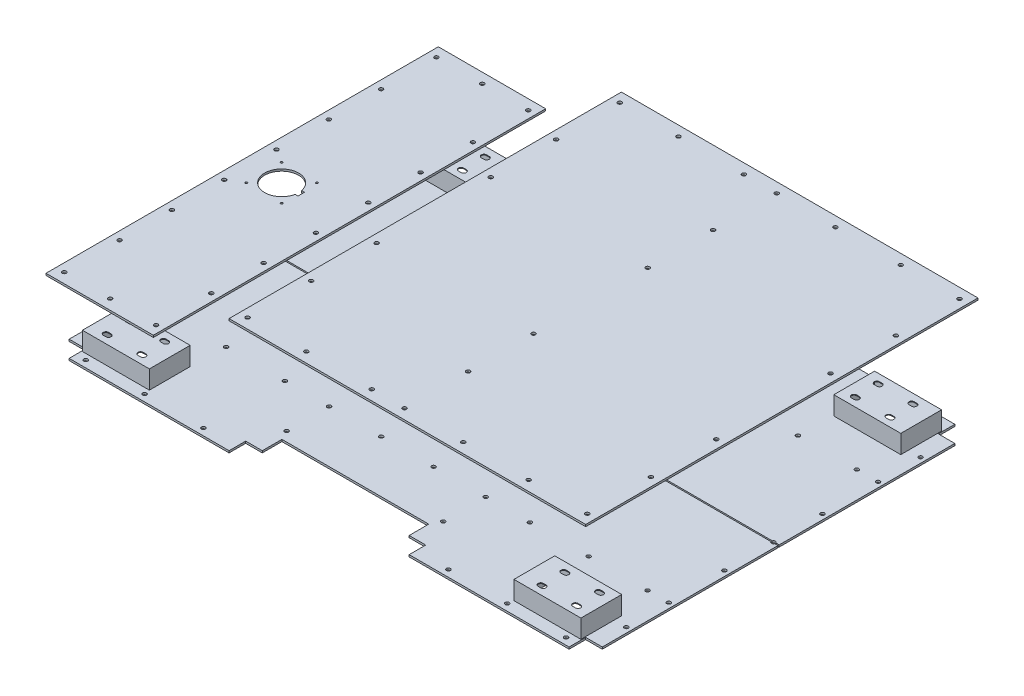
SolidWorks part; units mm, degrees
ref_plane "Front Plane" through (0, 0, 0) normal (0, 0, 1) x (1, 0, 0)
ref_plane "Top Plane" through (0, 0, 0) normal (0, 1, 0) x (1, 0, 0)
ref_plane "Right Plane" through (0, 0, 0) normal (1, 0, 0) x (0, 0, -1)
sketch "Sketch2" plane through (0, 422.0595, 0) normal (0, 1, 0) x (1, 0, 0)
  line L0 (436.2951, -933.6952) -> (410.8951, -933.6952) construction
  line L9 (436.2951, -933.6952) -> (410.8951, -933.6952) construction
  line L11 (196.2951, -933.6952) -> (196.2951, -903.6952) construction
  line L19 (196.2951, -834.4952) -> (196.2951, -933.6952) construction
  line L21 (196.2951, -903.6952) -> (410.8951, -903.6952) construction
  line L22 (410.8951, -933.6952) -> (410.8951, -834.4952) construction
  line L72 (410.8951, -903.6952) -> (410.8951, -933.6952) construction
  line L73 (436.2951, -959.0952) -> (436.2951, -933.6952) construction
  line L76 (690.8951, -959.0952) -> (436.2951, -959.0952) construction
  line L78 (690.8951, -933.6952) -> (690.8951, -959.0952) construction
  line L79 (410.8951, -384.4952) -> (436.2951, -384.4952) construction
  line L80 (436.2951, -384.4952) -> (436.2951, -359.0952) construction
  line L81 (436.2951, -359.0952) -> (690.8951, -359.0952) construction
  line L82 (436.2951, -959.0952) -> (436.2951, -933.6952) construction
  line L83 (690.8951, -959.0952) -> (436.2951, -959.0952) construction
  line L84 (690.8951, -933.6952) -> (690.8951, -959.0952) construction
  line L85 (690.8951, -359.0952) -> (690.8951, -384.4952) construction
  line L86 (690.8951, -384.4952) -> (716.2951, -384.4952) construction
  line L87 (716.2951, -384.4952) -> (716.2951, -933.6952) construction
  line L88 (716.2951, -933.6952) -> (690.8951, -933.6952) construction
  line L89 (410.8951, -384.4952) -> (436.2951, -384.4952) construction
  line L90 (436.2951, -384.4952) -> (436.2951, -359.0952) construction
  line L91 (436.2951, -359.0952) -> (690.8951, -359.0952) construction
  line L92 (690.8951, -359.0952) -> (690.8951, -384.4952) construction
  line L93 (690.8951, -384.4952) -> (716.2951, -384.4952) construction
  line L94 (716.2951, -384.4952) -> (716.2951, -658.0952) construction
  line L95 (716.2951, -933.6952) -> (690.8951, -933.6952) construction
  line L96 (196.2951, -933.6952) -> (170.8951, -933.6952) construction
  line L97 (170.8951, -933.6952) -> (170.8951, -959.0952) construction
  line L98 (170.8951, -959.0952) -> (-83.7049, -959.0952) construction
  line L99 (-83.7049, -959.0952) -> (-83.7049, -933.6952) construction
  line L100 (-83.7049, -933.6952) -> (-109.1049, -933.6952) construction
  line L101 (-109.1049, -933.6952) -> (-109.1049, -384.4952) construction
  line L102 (-109.1049, -384.4952) -> (-83.7049, -384.4952) construction
  line L103 (-83.7049, -384.4952) -> (-83.7049, -359.0952) construction
  line L104 (-83.7049, -359.0952) -> (170.8951, -359.0952) construction
  line L105 (170.8951, -359.0952) -> (170.8951, -384.4952) construction
  line L106 (170.8951, -384.4952) -> (196.2951, -384.4952) construction
  line L107 (196.2951, -933.6952) -> (170.8951, -933.6952) construction
  line L108 (170.8951, -933.6952) -> (170.8951, -959.0952) construction
  line L109 (170.8951, -959.0952) -> (-83.7049, -959.0952) construction
  line L110 (-83.7049, -959.0952) -> (-83.7049, -933.6952) construction
  line L111 (-83.7049, -933.6952) -> (-109.1049, -933.6952) construction
  line L112 (-109.1049, -933.6952) -> (-109.1049, -660.0952) construction
  line L113 (-109.1049, -384.4952) -> (-83.7049, -384.4952) construction
  line L114 (-83.7049, -384.4952) -> (-83.7049, -359.0952) construction
  line L115 (-83.7049, -359.0952) -> (170.8951, -359.0952) construction
  line L116 (170.8951, -359.0952) -> (170.8951, -384.4952) construction
  line L117 (170.8951, -384.4952) -> (196.2951, -384.4952) construction
  line L118 (716.2951, -659.0952) -> (-109.1049, -659.0952) construction
  line L119 (196.2951, -384.4952) -> (196.2951, -414.4952) construction
  line L120 (196.2951, -384.4952) -> (196.2951, -483.6952) construction
  line L121 (196.2951, -414.4952) -> (410.8951, -414.4952) construction
  line L122 (410.8951, -483.6952) -> (410.8951, -384.4952) construction
  line L123 (410.8951, -414.4952) -> (410.8951, -384.4952) construction
  line L124 (716.2951, -658.0952) -> (-109.1049, -658.0952) construction
  line L125 (716.2951, -660.0952) -> (-109.1049, -660.0952) construction
  line L126 (716.2951, -660.0952) -> (716.2951, -933.6952) construction
  line L127 (-109.1049, -658.0952) -> (-109.1049, -384.4952) construction
  line L128 (711.2951, -660.0952) -> (711.2951, -928.6952)
  line L129 (711.2951, -928.6952) -> (685.8951, -928.6952)
  line L130 (685.8951, -928.6952) -> (685.8951, -954.0952)
  line L131 (685.8951, -954.0952) -> (441.2951, -954.0952)
  line L132 (441.2951, -954.0952) -> (441.2951, -928.6952)
  line L133 (441.2951, -928.6952) -> (415.8951, -928.6952)
  line L134 (415.8951, -898.6952) -> (415.8951, -928.6952)
  line L135 (191.2951, -898.6952) -> (415.8951, -898.6952)
  line L136 (191.2951, -928.6952) -> (191.2951, -898.6952)
  line L137 (191.2951, -928.6952) -> (165.8951, -928.6952)
  line L138 (165.8951, -928.6952) -> (165.8951, -954.0952)
  line L139 (165.8951, -954.0952) -> (-78.7049, -954.0952)
  line L140 (-78.7049, -954.0952) -> (-78.7049, -928.6952)
  line L141 (-78.7049, -928.6952) -> (-104.1049, -928.6952)
  line L142 (-104.1049, -928.6952) -> (-104.1049, -660.0952)
  line L143 (-104.1049, -658.0952) -> (-104.1049, -389.4952)
  line L144 (-104.1049, -389.4952) -> (-78.7049, -389.4952)
  line L145 (-78.7049, -389.4952) -> (-78.7049, -364.0952)
  line L146 (-78.7049, -364.0952) -> (165.8951, -364.0952)
  line L147 (165.8951, -364.0952) -> (165.8951, -389.4952)
  line L148 (165.8951, -389.4952) -> (191.2951, -389.4952)
  line L149 (191.2951, -389.4952) -> (191.2951, -419.4952)
  line L150 (191.2951, -419.4952) -> (415.8951, -419.4952)
  line L151 (415.8951, -419.4952) -> (415.8951, -389.4952)
  line L152 (415.8951, -389.4952) -> (441.2951, -389.4952)
  line L153 (441.2951, -389.4952) -> (441.2951, -364.0952)
  line L154 (441.2951, -364.0952) -> (685.8951, -364.0952)
  line L155 (685.8951, -364.0952) -> (685.8951, -389.4952)
  line L156 (685.8951, -389.4952) -> (711.2951, -389.4952)
  line L157 (711.2951, -389.4952) -> (711.2951, -658.0952)
  line L158 (-104.1049, -660.0952) -> (711.2951, -660.0952)
  line L159 (711.2951, -658.0952) -> (-104.1049, -658.0952)
  circle A0 centre (703.3951, -434.0952) radius 3 construction
  circle A1 centre (703.3951, -499.0952) radius 3 construction
  circle A2 centre (183.7951, -884.0952) radius 3 construction
  circle A3 centre (183.7951, -819.0952) radius 3 construction
  circle A5 centre (703.3951, -499.0952) radius 3
  circle A6 centre (703.3951, -434.0952) radius 3
  circle A7 centre (703.3951, -819.0952) radius 3 construction
  circle A8 centre (703.3951, -734.0952) radius 3 construction
  circle A9 centre (703.3951, -659.0952) radius 3 construction
  circle A10 centre (703.3951, -584.0952) radius 3 construction
  circle A11 centre (703.3951, -819.0952) radius 3
  circle A12 centre (703.3951, -734.0952) radius 3
  circle A13 centre (703.3951, -659.0952) radius 3
  circle A14 centre (703.3951, -584.0952) radius 3
  circle A15 centre (703.3951, -884.0952) radius 3 construction
  circle A16 centre (703.3951, -884.0952) radius 3
  circle A17 centre (116.2951, -943.6952) radius 3 construction
  circle A18 centre (490.8951, -943.6952) radius 3 construction
  circle A19 centre (580.8951, -943.6952) radius 3 construction
  circle A20 centre (670.8951, -943.6952) radius 3 construction
  circle A21 centre (116.2951, -943.6952) radius 3
  circle A22 centre (490.8951, -943.6952) radius 3
  circle A23 centre (580.8951, -943.6952) radius 3
  circle A24 centre (670.8951, -943.6952) radius 3
  circle A25 centre (26.2951, -943.6952) radius 3 construction
  circle A26 centre (26.2951, -943.6952) radius 3
  circle A27 centre (-63.7049, -943.6952) radius 3 construction
  circle A28 centre (-63.7049, -943.6952) radius 3
  circle A29 centre (-63.7049, -819.0952) radius 3 construction
  circle A30 centre (-96.2049, -884.0952) radius 3 construction
  circle A31 centre (-63.7049, -819.0952) radius 3
  circle A32 centre (-96.2049, -884.0952) radius 3
  circle A33 centre (-96.2049, -434.0952) radius 3 construction
  circle A34 centre (-96.2049, -584.0952) radius 3 construction
  circle A35 centre (-96.2049, -659.0952) radius 3 construction
  circle A36 centre (-96.2049, -734.0952) radius 3 construction
  circle A37 centre (-96.2049, -819.0952) radius 3 construction
  circle A38 centre (-96.2049, -434.0952) radius 3
  circle A39 centre (-96.2049, -584.0952) radius 3
  circle A40 centre (-96.2049, -659.0952) radius 3
  circle A41 centre (-96.2049, -734.0952) radius 3
  circle A42 centre (-96.2049, -819.0952) radius 3
  circle A43 centre (-96.2049, -499.0952) radius 3 construction
  circle A44 centre (26.2951, -499.0952) radius 3 construction
  circle A45 centre (-63.7049, -499.0952) radius 3 construction
  circle A46 centre (26.2951, -499.0952) radius 3
  circle A47 centre (-63.7049, -499.0952) radius 3
  circle A48 centre (-96.2049, -499.0952) radius 3
  circle A49 centre (116.2951, -499.0952) radius 3 construction
  circle A50 centre (116.2951, -499.0952) radius 3
  circle A51 centre (-63.7049, -374.4952) radius 3 construction
  circle A52 centre (26.2951, -374.4952) radius 3 construction
  circle A53 centre (116.2951, -374.4952) radius 3 construction
  circle A54 centre (-63.7049, -374.4952) radius 3
  circle A55 centre (26.2951, -374.4952) radius 3
  circle A56 centre (116.2951, -374.4952) radius 3
  circle A57 centre (183.7951, -584.0952) radius 3 construction
  circle A58 centre (183.7951, -499.0952) radius 3 construction
  circle A59 centre (183.7951, -434.0952) radius 3 construction
  circle A60 centre (183.7951, -584.0952) radius 3
  circle A61 centre (183.7951, -499.0952) radius 3
  circle A62 centre (183.7951, -434.0952) radius 3
  circle A63 centre (183.7951, -659.0952) radius 3 construction
  circle A64 centre (183.7951, -659.0952) radius 3
  circle A65 centre (183.7951, -734.0952) radius 3 construction
  circle A66 centre (183.7951, -734.0952) radius 3
  circle A67 centre (263.5951, -819.0952) radius 3 construction
  circle A68 centre (183.7951, -884.0952) radius 3
  circle A69 centre (183.7951, -819.0952) radius 3
  circle A70 centre (263.5951, -819.0952) radius 3
  circle A71 centre (343.5951, -819.0952) radius 3 construction
  circle A72 centre (343.5951, -819.0952) radius 3
  circle A73 centre (423.3951, -884.0952) radius 3 construction
  circle A74 centre (423.3951, -819.0952) radius 3 construction
  circle A75 centre (490.8951, -819.0952) radius 3 construction
  circle A76 centre (423.3951, -734.0952) radius 3 construction
  circle A77 centre (423.3951, -884.0952) radius 3
  circle A78 centre (423.3951, -819.0952) radius 3
  circle A79 centre (490.8951, -819.0952) radius 3
  circle A80 centre (423.3951, -734.0952) radius 3
  circle A81 centre (423.3951, -659.0952) radius 3 construction
  circle A82 centre (423.3951, -659.0952) radius 3
  circle A83 centre (670.8951, -819.0952) radius 3 construction
  circle A84 centre (580.8951, -819.0952) radius 3 construction
  circle A85 centre (670.8951, -819.0952) radius 3
  circle A86 centre (580.8951, -819.0952) radius 3
  circle A87 centre (490.8951, -374.4952) radius 3 construction
  circle A88 centre (580.8951, -374.4952) radius 3 construction
  circle A89 centre (670.8951, -374.4952) radius 3 construction
  circle A90 centre (490.8951, -374.4952) radius 3
  circle A91 centre (580.8951, -374.4952) radius 3
  circle A92 centre (670.8951, -374.4952) radius 3
  circle A93 centre (423.3951, -584.0952) radius 3 construction
  circle A94 centre (423.3951, -584.0952) radius 3
  circle A95 centre (423.3951, -434.0952) radius 3 construction
  circle A96 centre (423.3951, -434.0952) radius 3
  circle A97 centre (423.3951, -499.0952) radius 3 construction
  circle A98 centre (423.3951, -499.0952) radius 3
  circle A99 centre (343.5951, -499.0952) radius 3 construction
  circle A100 centre (343.5951, -499.0952) radius 3
  circle A101 centre (263.5951, -499.0952) radius 3 construction
  circle A102 centre (263.5951, -499.0952) radius 3
  circle A103 centre (670.8951, -499.0952) radius 3 construction
  circle A104 centre (580.8951, -499.0952) radius 3 construction
  circle A105 centre (490.8951, -499.0952) radius 3 construction
  circle A106 centre (670.8951, -499.0952) radius 3
  circle A107 centre (580.8951, -499.0952) radius 3
  circle A108 centre (490.8951, -499.0952) radius 3
  circle A109 centre (116.2951, -819.0952) radius 3 construction
  circle A110 centre (26.2951, -819.0952) radius 3 construction
  circle A111 centre (116.2951, -819.0952) radius 3
  circle A112 centre (26.2951, -819.0952) radius 3
  point P56 (712.1088, -386.4469)
  point P57 (713.2951, -659.0952)
  point P72 (-106.1049, -387.4952)
  point P73 (-106.1049, -930.6952)
  point P88 (0, 0)
  point P90 (-109.1049, -658.0952)
  point P92 (-109.1049, -660.0952)
  dimension "D1" = 30
  dimension "D2" = 30
  dimension "D5" = 300
  dimension "D6" = 5
  dimension "D3" = 1
  dimension "D4" = 1
extrude "Boss-Extrude1" add sketch "Sketch2" along normal blind 3
sketch "Sketch4" plane through (0, 602.0595, 0) normal (0, 1, 0) x (1, 0, 0)
  line L0 (716.2951, -359.0952) -> (170.8951, -359.0952) construction
  line L1 (170.8951, -359.0952) -> (170.8951, -959.0952) construction
  line L2 (170.8951, -933.6952) -> (170.8951, -384.4952) construction
  line L3 (716.2951, -959.0952) -> (716.2951, -359.0952) construction
  line L4 (170.8951, -959.0952) -> (716.2951, -959.0952) construction
  line L5 (716.2951, -359.0952) -> (170.8951, -359.0952)
  line L6 (170.8951, -359.0952) -> (170.8951, -959.0952)
  line L7 (170.8951, -933.6952) -> (170.8951, -384.4952)
  line L8 (716.2951, -959.0952) -> (716.2951, -359.0952)
  line L9 (170.8951, -959.0952) -> (716.2951, -959.0952)
  line L10 (170.8951, -359.0952) -> (716.2951, -959.0952) construction
  line L11 (170.8951, -959.0952) -> (716.2951, -359.0952) construction
  line L12 (443.5951, -659.0952) -> (716.2951, -659.0952) construction
  circle A1 centre (613.5951, -943.6952) radius 3 construction
  circle A2 centre (703.3951, -943.6952) radius 3 construction
  circle A3 centre (513.5951, -943.6952) radius 3 construction
  circle A4 centre (703.3951, -846.3952) radius 3 construction
  circle A5 centre (703.3951, -746.3952) radius 3 construction
  circle A6 centre (423.7951, -943.6952) radius 3 construction
  circle A7 centre (423.7951, -846.3952) radius 3 construction
  circle A8 centre (373.5951, -943.6952) radius 3 construction
  circle A9 centre (273.5951, -943.6952) radius 3 construction
  circle A10 centre (183.7951, -943.6952) radius 3 construction
  circle A11 centre (183.7951, -746.3952) radius 3 construction
  circle A12 centre (183.7951, -846.3952) radius 3 construction
  circle A13 centre (423.7951, -746.3952) radius 3 construction
  circle A14 centre (423.7951, -746.3952) radius 3
  circle A15 centre (183.7951, -846.3952) radius 3
  circle A16 centre (183.7951, -746.3952) radius 3
  circle A17 centre (183.7951, -943.6952) radius 3
  circle A18 centre (273.5951, -943.6952) radius 3
  circle A19 centre (373.5951, -943.6952) radius 3
  circle A20 centre (423.7951, -846.3952) radius 3
  circle A21 centre (423.7951, -943.6952) radius 3
  circle A22 centre (703.3951, -746.3952) radius 3
  circle A23 centre (703.3951, -846.3952) radius 3
  circle A24 centre (513.5951, -943.6952) radius 3
  circle A25 centre (703.3951, -943.6952) radius 3
  circle A26 centre (613.5951, -943.6952) radius 3
  circle A40 centre (613.5951, -374.4952) radius 3
  circle A41 centre (703.3951, -374.4952) radius 3
  circle A42 centre (513.5951, -374.4952) radius 3
  circle A43 centre (703.3951, -471.7952) radius 3
  circle A44 centre (703.3951, -571.7952) radius 3
  circle A45 centre (423.7951, -374.4952) radius 3
  circle A46 centre (423.7951, -471.7952) radius 3
  circle A47 centre (373.5951, -374.4952) radius 3
  circle A48 centre (273.5951, -374.4952) radius 3
  circle A49 centre (183.7951, -374.4952) radius 3
  circle A50 centre (183.7951, -571.7952) radius 3
  circle A51 centre (183.7951, -471.7952) radius 3
  circle A52 centre (423.7951, -571.7952) radius 3
extrude "Boss-Extrude2" add sketch "Sketch4" along normal blind 3 separate body contours L5 L6 L9 L8 | A49 | A48 | A47 | A46 | A51 | A50 | A52 | A45 | A42 | A40 | A41 | A43 | A44 | A22 | A14 | A16 | A15 | A18 | A19 | A20 | A21 | A24 | A26 | A23 | A25 | A17
sketch "Sketch6" plane through (0, 522.0595, 0) normal (0, 1, 0) x (1, 0, 0)
  line L0 (-109.1049, -959.0952) -> (-109.1049, -359.0952) construction
  line L1 (55.0951, -384.4952) -> (55.0951, -933.6952) construction
  line L2 (-109.1049, -959.0952) -> (-109.1049, -359.0952)
  line L3 (55.0951, -384.4952) -> (55.0951, -933.6952)
  line L4 (55.0951, -933.6952) -> (55.0951, -959.0952)
  line L5 (170.8951, -959.0952) -> (-109.1049, -959.0952) construction
  line L6 (55.0951, -959.0952) -> (-109.1049, -959.0952)
  line L7 (55.0951, -384.4952) -> (55.0951, -359.0952)
  line L8 (170.8951, -359.0952) -> (-109.1049, -359.0952) construction
  line L9 (55.0951, -359.0952) -> (-109.1049, -359.0952)
  line L10 (55.0951, -659.0952) -> (-109.1049, -659.0952) construction
  circle A0 centre (-96.6049, -943.6952) radius 3 construction
  circle A1 centre (-26.3999, -943.6952) radius 3 construction
  circle A2 centre (43.7951, -943.6952) radius 3 construction
  circle A3 centre (-96.6049, -943.6952) radius 3
  circle A4 centre (-26.3999, -943.6952) radius 3
  circle A5 centre (43.7951, -943.6952) radius 3
  circle A6 centre (-96.6049, -859.0952) radius 3 construction
  circle A7 centre (43.7951, -859.0952) radius 3 construction
  circle A8 centre (-96.6049, -859.0952) radius 3
  circle A9 centre (43.7951, -859.0952) radius 3
  circle A10 centre (43.7951, -699.0952) radius 3 construction
  circle A11 centre (-96.6049, -699.0952) radius 3 construction
  circle A12 centre (43.7951, -779.0952) radius 3 construction
  circle A13 centre (-96.6049, -779.0952) radius 3 construction
  circle A14 centre (43.7951, -699.0952) radius 3
  circle A15 centre (-96.6049, -699.0952) radius 3
  circle A16 centre (43.7951, -779.0952) radius 3
  circle A17 centre (-96.6049, -779.0952) radius 3
  circle A27 centre (-96.6049, -619.0952) radius 3
  circle A28 centre (-96.6049, -539.0952) radius 3
  circle A29 centre (43.7951, -539.0952) radius 3
  circle A30 centre (43.7951, -619.0952) radius 3
  circle A31 centre (43.7951, -459.0952) radius 3
  circle A32 centre (-96.6049, -459.0952) radius 3
  circle A33 centre (43.7951, -374.4952) radius 3
  circle A34 centre (-26.3999, -374.4952) radius 3
  circle A35 centre (-96.6049, -374.4952) radius 3
extrude "Boss-Extrude3" add sketch "Sketch6" along normal blind 3 separate body
sketch "Sketch9" plane through (0, 525.0595, 0) normal (0, 1, 0) x (1, 0, 0)
  line L0 (-48.7049, -659.0952) -> (-22.7049, -659.0952) construction
  line L1 (-48.7049, -654.0952) -> (-22.7049, -654.0952) construction
  line L2 (-48.7049, -664.0952) -> (-22.7049, -664.0952) construction
  line L3 (-23.1902, -654.0952) -> (-18.6902, -654.0952)
  line L4 (-18.6902, -654.0952) -> (-18.6902, -664.0952)
  line L5 (-18.6902, -664.0952) -> (-23.1902, -664.0952)
  line L6 (-109.1049, -359.0952) -> (-109.1049, -959.0952) construction
  line L7 (-109.1049, -959.0952) -> (55.0951, -959.0952) construction
  arc A0 (-23.1902, -654.0952) -> (-23.1902, -664.0952) centre (-48.7049, -659.0952) ccw
  dimension "D1" = 26
  dimension "D4" = 300
  dimension "D5" = 90.4147
  dimension "D2" = 60.4
  dimension "D3" = 85.9147
extrude "Cut-Extrude1" cut sketch "Sketch9" against normal up to next (3 mm away)
sketch "Sketch10" plane through (0, 525.0595, 0) normal (0, 1, 0) x (1, 0, 0)
  line L0 (-109.1049, -359.0952) -> (-109.1049, -959.0952) construction
  line L1 (-109.1049, -959.0952) -> (55.0951, -959.0952) construction
  circle A0 centre (-21.7049, -632.0952) radius 1.6
  circle A1 centre (-21.7049, -686.0952) radius 1.6
  circle A2 centre (-75.7049, -632.0952) radius 1.6
  circle A3 centre (-75.7049, -686.0952) radius 1.6
  dimension "D1" = 3.2
  dimension "D2" = 33.4
  dimension "D3" = 87.4
  dimension "D4" = 273
  dimension "D5" = 327
extrude "Cut-Extrude4" cut sketch "Sketch10" against normal up to next (3 mm away)
sketch "Sketch13" plane through (0, 422.0595, 0) normal (0, -1, 0) x (1, 0, 0)
  line L1 (683.5951, 933.6952) -> (583.5951, 933.6952)
  line L3 (683.5951, 873.6952) -> (583.5951, 873.6952)
  line L4 (583.5951, 933.6952) -> (583.5951, 873.6952)
  line L7 (303.5951, 901.0952) -> (303.5951, 417.0952) construction
  line L9 (-104.1049, 928.6952) -> (-104.1049, 660.0952) construction
  line L22 (683.5951, 933.6952) -> (683.5951, 873.6952)
  line L23 (-104.1049, 660.0952) -> (-99.0333, 660.0952) construction
  line L26 (303.5951, 659.0952) -> (712.9729, 659.0952) construction
  line L30 (683.5951, 384.4952) -> (683.5951, 444.4952)
  line L31 (583.5951, 384.4952) -> (583.5951, 444.4952)
  line L32 (683.5951, 444.4952) -> (583.5951, 444.4952)
  line L33 (683.5951, 384.4952) -> (583.5951, 384.4952)
  line L34 (-76.4049, 933.6952) -> (-76.4049, 873.6952)
  line L35 (23.5951, 933.6952) -> (23.5951, 873.6952)
  line L36 (-76.4049, 873.6952) -> (23.5951, 873.6952)
  line L37 (-76.4049, 933.6952) -> (23.5951, 933.6952)
  line L38 (-76.4049, 384.4952) -> (23.5951, 384.4952)
  line L39 (-76.4049, 444.4952) -> (23.5951, 444.4952)
  line L40 (23.5951, 384.4952) -> (23.5951, 444.4952)
  line L41 (-76.4049, 384.4952) -> (-76.4049, 444.4952)
  dimension "D1" = 27.7
  dimension "D2" = 127.7
  dimension "D3" = 407.7
  dimension "D4" = 687.7
  dimension "D5" = 213.6
  dimension "D6" = 273.6
  dimension "D7" = 1
  dimension "D8" = 215.6
extrude "Cut-Extrude6" cut sketch "Sketch13" along direction (0, 1, 0) on the side against the normal up to surface (3 mm away)
sketch "Sketch15" plane through (0, 422.0595, 0) normal (0, -1, 0) x (1, 0, 0)
  line L0 (583.5951, 933.6952) -> (583.5951, 873.6952) construction
  line L1 (583.5951, 873.6952) -> (683.5951, 873.6952) construction
  line L2 (683.5951, 933.6952) -> (583.5951, 933.6952) construction
  line L3 (683.5951, 873.6952) -> (683.5951, 933.6952) construction
  line L4 (583.5951, 933.6952) -> (583.5951, 873.6952)
  line L5 (583.5951, 873.6952) -> (683.5951, 873.6952)
  line L6 (683.5951, 933.6952) -> (583.5951, 933.6952)
  line L7 (683.5951, 873.6952) -> (683.5951, 933.6952)
  line L8 (582.3951, 934.8952) -> (582.3951, 872.4952)
  line L9 (582.3951, 872.4952) -> (684.7951, 872.4952)
  line L10 (684.7951, 872.4952) -> (684.7951, 934.8952)
  line L11 (684.7951, 934.8952) -> (582.3951, 934.8952)
  line L12 (716.2951, 659.0952) -> (-109.1049, 659.0952) construction
  line L13 (716.2951, 384.4952) -> (716.2951, 933.6952) construction
  line L15 (-109.1049, 933.6952) -> (-109.1049, 384.4952) construction
  line L40 (303.5951, 659.0952) -> (303.5951, 898.6952) construction
  line L41 (191.2951, 898.6952) -> (415.8951, 898.6952) construction
  line L42 (684.7951, 383.2952) -> (582.3951, 383.2952)
  line L43 (684.7951, 445.6952) -> (684.7951, 383.2952)
  line L44 (582.3951, 445.6952) -> (684.7951, 445.6952)
  line L45 (582.3951, 383.2952) -> (582.3951, 445.6952)
  line L46 (683.5951, 444.4952) -> (683.5951, 384.4952)
  line L47 (683.5951, 384.4952) -> (583.5951, 384.4952)
  line L48 (583.5951, 444.4952) -> (683.5951, 444.4952)
  line L49 (583.5951, 384.4952) -> (583.5951, 444.4952)
  line L50 (23.5951, 384.4952) -> (23.5951, 444.4952)
  line L51 (23.5951, 444.4952) -> (-76.4049, 444.4952)
  line L52 (-76.4049, 384.4952) -> (23.5951, 384.4952)
  line L53 (-76.4049, 444.4952) -> (-76.4049, 384.4952)
  line L54 (24.7951, 383.2952) -> (24.7951, 445.6952)
  line L55 (24.7951, 445.6952) -> (-77.6049, 445.6952)
  line L56 (-77.6049, 445.6952) -> (-77.6049, 383.2952)
  line L57 (-77.6049, 383.2952) -> (24.7951, 383.2952)
  line L58 (-77.6049, 934.8952) -> (24.7951, 934.8952)
  line L59 (-77.6049, 872.4952) -> (-77.6049, 934.8952)
  line L60 (24.7951, 872.4952) -> (-77.6049, 872.4952)
  line L61 (24.7951, 934.8952) -> (24.7951, 872.4952)
  line L62 (-76.4049, 873.6952) -> (-76.4049, 933.6952)
  line L63 (-76.4049, 933.6952) -> (23.5951, 933.6952)
  line L64 (23.5951, 873.6952) -> (-76.4049, 873.6952)
  line L65 (23.5951, 933.6952) -> (23.5951, 873.6952)
  dimension "D1" = 1.2
extrude "Boss-Extrude4" add sketch "Sketch15" against normal blind 27 from surface at -3 starting at face at (633.5951, 425.0595, 414.4952)
sketch "Sketch16" plane through (0, 452.0595, 0) normal (0, 1, 0) x (-1, 0, 0)
  line L0 (-684.7951, 934.8952) -> (-582.3951, 934.8952) construction
  line L1 (-684.7951, 934.8952) -> (-582.3951, 934.8952)
  line L2 (-684.7951, 934.8952) -> (-684.7951, 872.4952)
  line L3 (-684.7951, 872.4952) -> (-582.3951, 872.4952)
  line L4 (-582.3951, 934.8952) -> (-582.3951, 872.4952)
  line L5 (-684.7951, 872.4952) -> (-684.7951, 934.8952) construction
  line L6 (-582.3951, 934.8952) -> (-582.3951, 872.4952) construction
  line L7 (-582.3951, 872.4952) -> (-684.7951, 872.4952) construction
  line L8 (-582.3951, 445.6952) -> (-582.3951, 383.2952) construction
  line L9 (-684.7951, 445.6952) -> (-582.3951, 445.6952)
  line L10 (-684.7951, 445.6952) -> (-684.7951, 383.2952)
  line L11 (-684.7951, 383.2952) -> (-582.3951, 383.2952)
  line L12 (-582.3951, 445.6952) -> (-582.3951, 383.2952)
  line L13 (-582.3951, 383.2952) -> (-684.7951, 383.2952) construction
  line L15 (-24.7951, 934.8952) -> (77.6049, 934.8952)
  line L16 (-24.7951, 934.8952) -> (-24.7951, 872.4952)
  line L17 (-24.7951, 872.4952) -> (77.6049, 872.4952)
  line L18 (77.6049, 934.8952) -> (77.6049, 872.4952)
  line L19 (77.6049, 445.6952) -> (77.6049, 383.2952) construction
  line L20 (-24.7951, 445.6952) -> (77.6049, 445.6952)
  line L21 (-24.7951, 445.6952) -> (-24.7951, 383.2952)
  line L22 (-24.7951, 383.2952) -> (77.6049, 383.2952)
  line L23 (77.6049, 445.6952) -> (77.6049, 383.2952)
extrude "Boss-Extrude5" add sketch "Sketch16" along normal blind 1.2
sketch "Sketch18" plane through (0, 453.2595, 0) normal (0, 1, 0) x (1, 0, 0)
  line L0 (657.0951, -401.4952) -> (653.0951, -401.4952) construction
  line L1 (653.0951, -393.4952) -> (657.0951, -393.4952) construction
  line L2 (604.0951, -393.4952) -> (600.0951, -393.4952) construction
  line L3 (600.0951, -401.4952) -> (604.0951, -401.4952) construction
  line L4 (653.0951, -428.4952) -> (657.0951, -428.4952) construction
  line L5 (657.0951, -436.4952) -> (653.0951, -436.4952) construction
  line L6 (600.0951, -436.4952) -> (604.0951, -436.4952) construction
  line L7 (604.0951, -428.4952) -> (600.0951, -428.4952) construction
  line L8 (657.0951, -401.4952) -> (653.0951, -401.4952)
  line L9 (653.0951, -393.4952) -> (657.0951, -393.4952)
  line L10 (604.0951, -393.4952) -> (600.0951, -393.4952)
  line L11 (600.0951, -401.4952) -> (604.0951, -401.4952)
  line L12 (653.0951, -428.4952) -> (657.0951, -428.4952)
  line L13 (657.0951, -436.4952) -> (653.0951, -436.4952)
  line L14 (600.0951, -436.4952) -> (604.0951, -436.4952)
  line L15 (604.0951, -428.4952) -> (600.0951, -428.4952)
  arc A0 (653.0951, -393.4952) -> (653.0951, -401.4952) centre (653.0951, -397.4952) ccw construction
  arc A1 (657.0951, -401.4952) -> (657.0951, -393.4952) centre (657.0951, -397.4952) ccw construction
  arc A2 (604.0951, -401.4952) -> (604.0951, -393.4952) centre (604.0951, -397.4952) ccw construction
  arc A3 (600.0951, -393.4952) -> (600.0951, -401.4952) centre (600.0951, -397.4952) ccw construction
  arc A4 (653.0951, -428.4952) -> (653.0951, -436.4952) centre (653.0951, -432.4952) ccw construction
  arc A5 (657.0951, -436.4952) -> (657.0951, -428.4952) centre (657.0951, -432.4952) ccw construction
  arc A6 (600.0951, -428.4952) -> (600.0951, -436.4952) centre (600.0951, -432.4952) ccw construction
  arc A7 (604.0951, -436.4952) -> (604.0951, -428.4952) centre (604.0951, -432.4952) ccw construction
  arc A8 (653.0951, -393.4952) -> (653.0951, -401.4952) centre (653.0951, -397.4952) ccw
  arc A9 (657.0951, -401.4952) -> (657.0951, -393.4952) centre (657.0951, -397.4952) ccw
  arc A10 (604.0951, -401.4952) -> (604.0951, -393.4952) centre (604.0951, -397.4952) ccw
  arc A11 (600.0951, -393.4952) -> (600.0951, -401.4952) centre (600.0951, -397.4952) ccw
  arc A12 (653.0951, -428.4952) -> (653.0951, -436.4952) centre (653.0951, -432.4952) ccw
  arc A13 (657.0951, -436.4952) -> (657.0951, -428.4952) centre (657.0951, -432.4952) ccw
  arc A14 (600.0951, -428.4952) -> (600.0951, -436.4952) centre (600.0951, -432.4952) ccw
  arc A15 (604.0951, -436.4952) -> (604.0951, -428.4952) centre (604.0951, -432.4952) ccw
extrude "Cut-Extrude7" cut sketch "Sketch18" along direction (0, 1, 0) on the side against the normal up to surface (28.2 mm away)
sketch "Sketch19" plane through (0, 453.2595, 0) normal (0, 1, 0) x (1, 0, 0)
  line L19 (614.0951, -882.6952) -> (610.0951, -882.6952) construction
  line L20 (610.0951, -890.6952) -> (614.0951, -890.6952) construction
  line L21 (663.0951, -882.6952) -> (667.0951, -882.6952) construction
  line L22 (667.0951, -890.6952) -> (663.0951, -890.6952) construction
  line L23 (614.0951, -917.6952) -> (610.0951, -917.6952) construction
  line L24 (610.0951, -925.6952) -> (614.0951, -925.6952) construction
  line L25 (663.0951, -917.6952) -> (667.0951, -917.6952) construction
  line L26 (667.0951, -925.6952) -> (663.0951, -925.6952) construction
  line L27 (614.0951, -882.6952) -> (610.0951, -882.6952)
  line L28 (610.0951, -890.6952) -> (614.0951, -890.6952)
  line L29 (663.0951, -882.6952) -> (667.0951, -882.6952)
  line L30 (667.0951, -890.6952) -> (663.0951, -890.6952)
  line L31 (614.0951, -917.6952) -> (610.0951, -917.6952)
  line L32 (610.0951, -925.6952) -> (614.0951, -925.6952)
  line L33 (663.0951, -917.6952) -> (667.0951, -917.6952)
  line L34 (667.0951, -925.6952) -> (663.0951, -925.6952)
  arc A19 (610.0951, -882.6952) -> (610.0951, -890.6952) centre (610.0951, -886.6952) ccw construction
  arc A20 (614.0951, -890.6952) -> (614.0951, -882.6952) centre (614.0951, -886.6952) ccw construction
  arc A21 (663.0951, -882.6952) -> (663.0951, -890.6952) centre (663.0951, -886.6952) ccw construction
  arc A22 (667.0951, -890.6952) -> (667.0951, -882.6952) centre (667.0951, -886.6952) ccw construction
  arc A23 (614.0951, -925.6952) -> (614.0951, -917.6952) centre (614.0951, -921.6952) ccw construction
  arc A24 (610.0951, -917.6952) -> (610.0951, -925.6952) centre (610.0951, -921.6952) ccw construction
  arc A25 (663.0951, -917.6952) -> (663.0951, -925.6952) centre (663.0951, -921.6952) ccw construction
  arc A26 (667.0951, -925.6952) -> (667.0951, -917.6952) centre (667.0951, -921.6952) ccw construction
  arc A27 (610.0951, -882.6952) -> (610.0951, -890.6952) centre (610.0951, -886.6952) ccw
  arc A28 (614.0951, -890.6952) -> (614.0951, -882.6952) centre (614.0951, -886.6952) ccw
  arc A29 (663.0951, -882.6952) -> (663.0951, -890.6952) centre (663.0951, -886.6952) ccw
  arc A30 (667.0951, -890.6952) -> (667.0951, -882.6952) centre (667.0951, -886.6952) ccw
  arc A31 (614.0951, -925.6952) -> (614.0951, -917.6952) centre (614.0951, -921.6952) ccw
  arc A32 (610.0951, -917.6952) -> (610.0951, -925.6952) centre (610.0951, -921.6952) ccw
  arc A33 (663.0951, -917.6952) -> (663.0951, -925.6952) centre (663.0951, -921.6952) ccw
  arc A34 (667.0951, -925.6952) -> (667.0951, -917.6952) centre (667.0951, -921.6952) ccw
extrude "Cut-Extrude8" cut sketch "Sketch19" against normal through all
sketch "Sketch21" plane through (0, 453.2595, 0) normal (0, 1, 0) x (1, 0, 0)
  line L0 (-50.9049, -917.6952) -> (-54.9049, -917.6952) construction
  line L1 (-54.9049, -925.6952) -> (-50.9049, -925.6952) construction
  line L2 (-50.9049, -882.6952) -> (-54.9049, -882.6952) construction
  line L3 (-54.9049, -890.6952) -> (-50.9049, -890.6952) construction
  line L4 (-1.9049, -882.6952) -> (2.0951, -882.6952) construction
  line L5 (2.0951, -890.6952) -> (-1.9049, -890.6952) construction
  line L6 (-1.9049, -917.6952) -> (2.0951, -917.6952) construction
  line L7 (2.0951, -925.6952) -> (-1.9049, -925.6952) construction
  line L8 (-50.9049, -917.6952) -> (-54.9049, -917.6952)
  line L9 (-54.9049, -925.6952) -> (-50.9049, -925.6952)
  line L10 (-50.9049, -882.6952) -> (-54.9049, -882.6952)
  line L11 (-54.9049, -890.6952) -> (-50.9049, -890.6952)
  line L12 (-1.9049, -882.6952) -> (2.0951, -882.6952)
  line L13 (2.0951, -890.6952) -> (-1.9049, -890.6952)
  line L14 (-1.9049, -917.6952) -> (2.0951, -917.6952)
  line L15 (2.0951, -925.6952) -> (-1.9049, -925.6952)
  arc A0 (-54.9049, -917.6952) -> (-54.9049, -925.6952) centre (-54.9049, -921.6952) ccw construction
  arc A1 (-50.9049, -925.6952) -> (-50.9049, -917.6952) centre (-50.9049, -921.6952) ccw construction
  arc A2 (-54.9049, -882.6952) -> (-54.9049, -890.6952) centre (-54.9049, -886.6952) ccw construction
  arc A3 (-50.9049, -890.6952) -> (-50.9049, -882.6952) centre (-50.9049, -886.6952) ccw construction
  arc A4 (-1.9049, -882.6952) -> (-1.9049, -890.6952) centre (-1.9049, -886.6952) ccw construction
  arc A5 (2.0951, -890.6952) -> (2.0951, -882.6952) centre (2.0951, -886.6952) ccw construction
  arc A6 (-1.9049, -917.6952) -> (-1.9049, -925.6952) centre (-1.9049, -921.6952) ccw construction
  arc A7 (2.0951, -925.6952) -> (2.0951, -917.6952) centre (2.0951, -921.6952) ccw construction
  arc A8 (-54.9049, -917.6952) -> (-54.9049, -925.6952) centre (-54.9049, -921.6952) ccw
  arc A9 (-50.9049, -925.6952) -> (-50.9049, -917.6952) centre (-50.9049, -921.6952) ccw
  arc A10 (-54.9049, -882.6952) -> (-54.9049, -890.6952) centre (-54.9049, -886.6952) ccw
  arc A11 (-50.9049, -890.6952) -> (-50.9049, -882.6952) centre (-50.9049, -886.6952) ccw
  arc A12 (-1.9049, -882.6952) -> (-1.9049, -890.6952) centre (-1.9049, -886.6952) ccw
  arc A13 (2.0951, -890.6952) -> (2.0951, -882.6952) centre (2.0951, -886.6952) ccw
  arc A14 (-1.9049, -917.6952) -> (-1.9049, -925.6952) centre (-1.9049, -921.6952) ccw
  arc A15 (2.0951, -925.6952) -> (2.0951, -917.6952) centre (2.0951, -921.6952) ccw
extrude "Cut-Extrude9" cut sketch "Sketch21" against normal through all
sketch "Sketch22" plane through (0, 453.2595, 0) normal (0, 1, 0) x (1, 0, 0)
  line L0 (-49.9049, -428.4952) -> (-53.9049, -428.4952) construction
  line L1 (-53.9049, -436.4952) -> (-49.9049, -436.4952) construction
  line L2 (-53.9049, -401.4952) -> (-49.9049, -401.4952) construction
  line L3 (-49.9049, -393.4952) -> (-53.9049, -393.4952) construction
  line L4 (-0.9049, -428.4952) -> (3.0951, -428.4952) construction
  line L5 (3.0951, -436.4952) -> (-0.9049, -436.4952) construction
  line L6 (3.0951, -401.4952) -> (-0.9049, -401.4952) construction
  line L7 (-0.9049, -393.4952) -> (3.0951, -393.4952) construction
  line L8 (-49.9049, -428.4952) -> (-53.9049, -428.4952)
  line L9 (-53.9049, -436.4952) -> (-49.9049, -436.4952)
  line L10 (-53.9049, -401.4952) -> (-49.9049, -401.4952)
  line L11 (-49.9049, -393.4952) -> (-53.9049, -393.4952)
  line L12 (-0.9049, -428.4952) -> (3.0951, -428.4952)
  line L13 (3.0951, -436.4952) -> (-0.9049, -436.4952)
  line L14 (3.0951, -401.4952) -> (-0.9049, -401.4952)
  line L15 (-0.9049, -393.4952) -> (3.0951, -393.4952)
  arc A0 (-53.9049, -428.4952) -> (-53.9049, -436.4952) centre (-53.9049, -432.4952) ccw construction
  arc A1 (-49.9049, -436.4952) -> (-49.9049, -428.4952) centre (-49.9049, -432.4952) ccw construction
  arc A2 (-53.9049, -393.4952) -> (-53.9049, -401.4952) centre (-53.9049, -397.4952) ccw construction
  arc A3 (-49.9049, -401.4952) -> (-49.9049, -393.4952) centre (-49.9049, -397.4952) ccw construction
  arc A4 (-0.9049, -428.4952) -> (-0.9049, -436.4952) centre (-0.9049, -432.4952) ccw construction
  arc A5 (3.0951, -436.4952) -> (3.0951, -428.4952) centre (3.0951, -432.4952) ccw construction
  arc A6 (-0.9049, -393.4952) -> (-0.9049, -401.4952) centre (-0.9049, -397.4952) ccw construction
  arc A7 (3.0951, -401.4952) -> (3.0951, -393.4952) centre (3.0951, -397.4952) ccw construction
  arc A8 (-53.9049, -428.4952) -> (-53.9049, -436.4952) centre (-53.9049, -432.4952) ccw
  arc A9 (-49.9049, -436.4952) -> (-49.9049, -428.4952) centre (-49.9049, -432.4952) ccw
  arc A10 (-53.9049, -393.4952) -> (-53.9049, -401.4952) centre (-53.9049, -397.4952) ccw
  arc A11 (-49.9049, -401.4952) -> (-49.9049, -393.4952) centre (-49.9049, -397.4952) ccw
  arc A12 (-0.9049, -428.4952) -> (-0.9049, -436.4952) centre (-0.9049, -432.4952) ccw
  arc A13 (3.0951, -436.4952) -> (3.0951, -428.4952) centre (3.0951, -432.4952) ccw
  arc A14 (-0.9049, -393.4952) -> (-0.9049, -401.4952) centre (-0.9049, -397.4952) ccw
  arc A15 (3.0951, -401.4952) -> (3.0951, -393.4952) centre (3.0951, -397.4952) ccw
extrude "Cut-Extrude10" cut sketch "Sketch22" against normal up to surface (1.2 mm away) up to face at (-26.4049, 452.0595, 414.4952)
